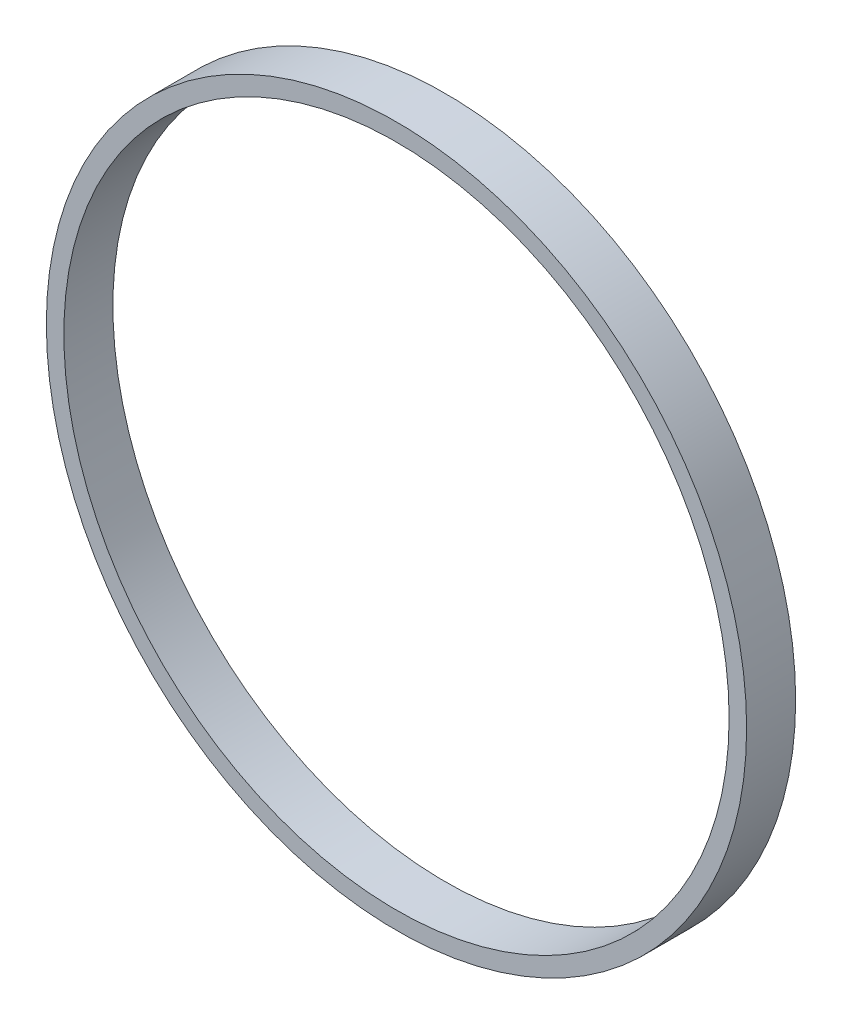
SolidWorks part; units mm, degrees
ref_plane "Front Plane" through (0, 0, 0) normal (0, 0, 1) x (1, 0, 0)
ref_plane "Top Plane" through (0, 0, 0) normal (0, 1, 0) x (1, 0, 0)
ref_plane "Right Plane" through (0, 0, 0) normal (1, 0, 0) x (0, 0, -1)
sketch "Sketch1" plane through (0, 0, 0) normal (0, 0, 1) x (1, 0, 0)
  circle A0 centre (0, 0) radius 50
  dimension "D1" = 100
extrude "Boss-Extrude1" add sketch "Sketch1" along normal blind 7 contours A0
sketch "Sketch2" plane through (0, 0, 7) normal (0, 0, 1) x (1, 0, 0)
  circle A0 centre (0, 0) radius 47.5
  dimension "D1" = 95
extrude "Cut-Extrude1" cut sketch "Sketch2" against normal blind 7
